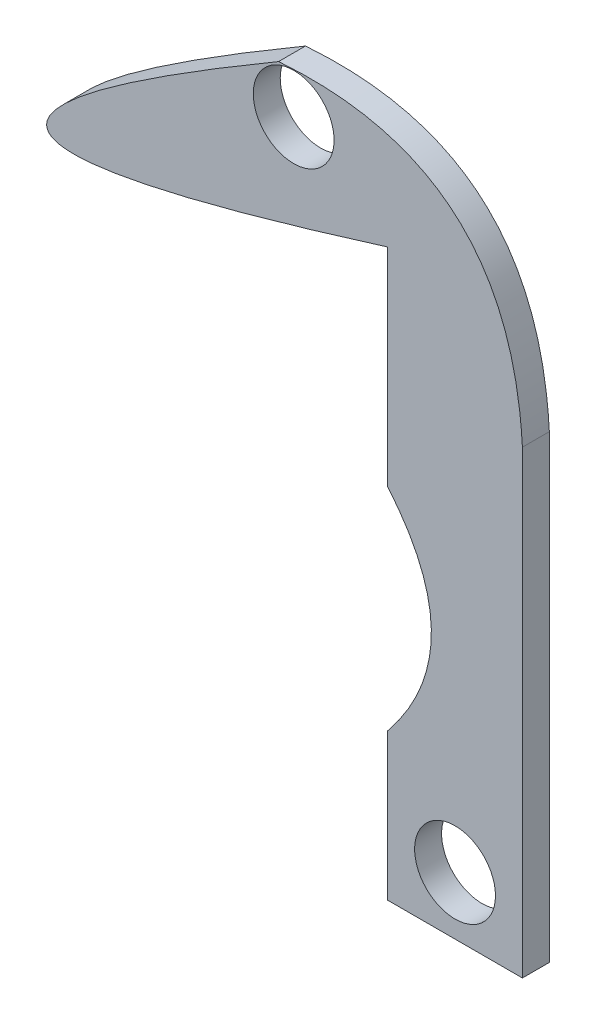
SolidWorks part; units mm, degrees
ref_plane "Front Plane" through (0, 0, 0) normal (0, 0, 1) x (1, 0, 0)
ref_plane "Top Plane" through (0, 0, 0) normal (0, 1, 0) x (1, 0, 0)
ref_plane "Right Plane" through (0, 0, 0) normal (1, 0, 0) x (0, 0, -1)
sketch "Esquisse1" plane through (0, 0, 0) normal (0, 0, 1) x (1, 0, 0)
  line L0 (0, 0) -> (10, 0)
  line L1 (10, 0) -> (10, 18)
  line L3 (0, 42) -> (0, 0)
  line L4 (10, 18) -> (10, 60)
  spline S0 degree 2 poles (10, 60) (-55.2265, 24.7256) (0, 42) knots 0 0 0 1 1 1
  dimension "D1" = 60
  dimension "D2" = 10
  dimension "D3" = 42
extrude "Boss.-Extru.1" add sketch "Esquisse1" along normal blind 2
sketch "Esquisse2" plane through (0, 0, 2) normal (0, 0, 1) x (1, 0, 0)
  line L0 (0, 0) -> (10, 0) construction
  circle A0 centre (5, 4.2885) radius 3
  point P4 (5, 0)
  dimension "D1" = 6
extrude "Enlèv. mat.-Extru.1" cut sketch "Esquisse2" against normal blind 2
sketch "Esquisse3" plane through (0, 0, 2) normal (0, 0, 1) x (1, 0, 0)
  line L0 (0, 42) -> (0, 0) construction
  line L1 (0, 26.5869) -> (0, 10.8956)
  spline S0 degree 2 poles (0, 26.5869) (6.4809, 18.9004) (0, 10.8956) knots 0 0 0 1 1 1
extrude "Enlèv. mat.-Extru.2" cut sketch "Esquisse3" against normal blind 10
sketch "Esquisse4" plane through (0, 0, 2) normal (0, 0, 1) x (1, 0, 0)
  line L0 (10, 0) -> (10, 60) construction
  line L1 (10, 34.1298) -> (10, 60)
  parabola Q10 (10, 60) -> (0, 42) focus (-24.9965, 37.0647) apex (-25.2689, 36.9458) construction
  parabola Q17 (10, 60) -> (0, 42) focus (-24.9965, 37.0647) apex (-25.2689, 36.9458) construction
  parabola Q18 (10, 60) -> (-8.105, 49.8724) focus (-24.9965, 37.0647) apex (-25.2689, 36.9458)
  parabola Q19 (10, 60) -> (0, 42) focus (-24.9965, 37.0647) apex (-25.2689, 36.9458) construction
  spline S0 degree 2 poles (10, 34.1298) (9.0704, 51.1756) (-8.105, 49.8724) knots 0 0 0 1 1 1
extrude "Enlèv. mat.-Extru.3" cut sketch "Esquisse4" against normal blind 10
sketch "Esquisse5" plane through (0, 0, 0) normal (0, 0, -1) x (-1, 0, 0)
  circle A0 centre (6.9796, 46.8724) radius 3
  dimension "D1" = 6
  dimension "D2" = 3
extrude "Enlèv. mat.-Extru.4" cut sketch "Esquisse5" against normal blind 10 contours A0
